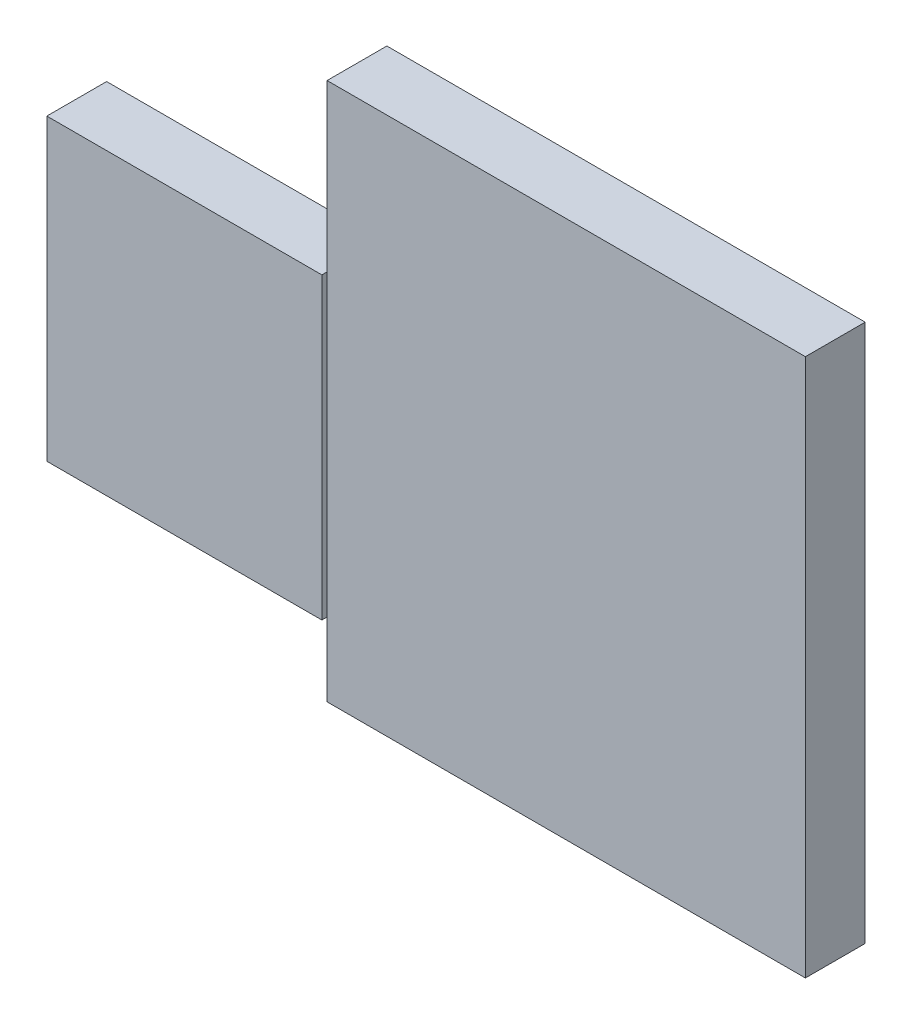
SolidWorks part; units mm, degrees
ref_plane "前视基准面" through (0, 0, 0) normal (0, 0, 1) x (1, 0, 0)
ref_plane "上视基准面" through (0, 0, 0) normal (0, 1, 0) x (1, 0, 0)
ref_plane "右视基准面" through (0, 0, 0) normal (1, 0, 0) x (0, 0, -1)
other "Configuration Table"
sketch "草图1" plane through (0, 0, 0) normal (0, 0, 1) x (1, 0, 0)
  line L1 (0, 0) -> (40, 0)
  line L2 (0, 0) -> (0, -45)
  line L3 (0, -45) -> (40, -45)
  line L4 (40, 0) -> (40, -45)
  line L5 (-0.4377, -39.2936) -> (-23.4377, -39.2936)
  line L6 (-0.4377, -39.2936) -> (-0.4377, -14.2936)
  line L7 (-0.4377, -14.2936) -> (-23.4377, -14.2936)
  line L8 (-23.4377, -39.2936) -> (-23.4377, -14.2936)
extrude "凸台-拉伸1" add sketch "草图1" along normal blind 5
